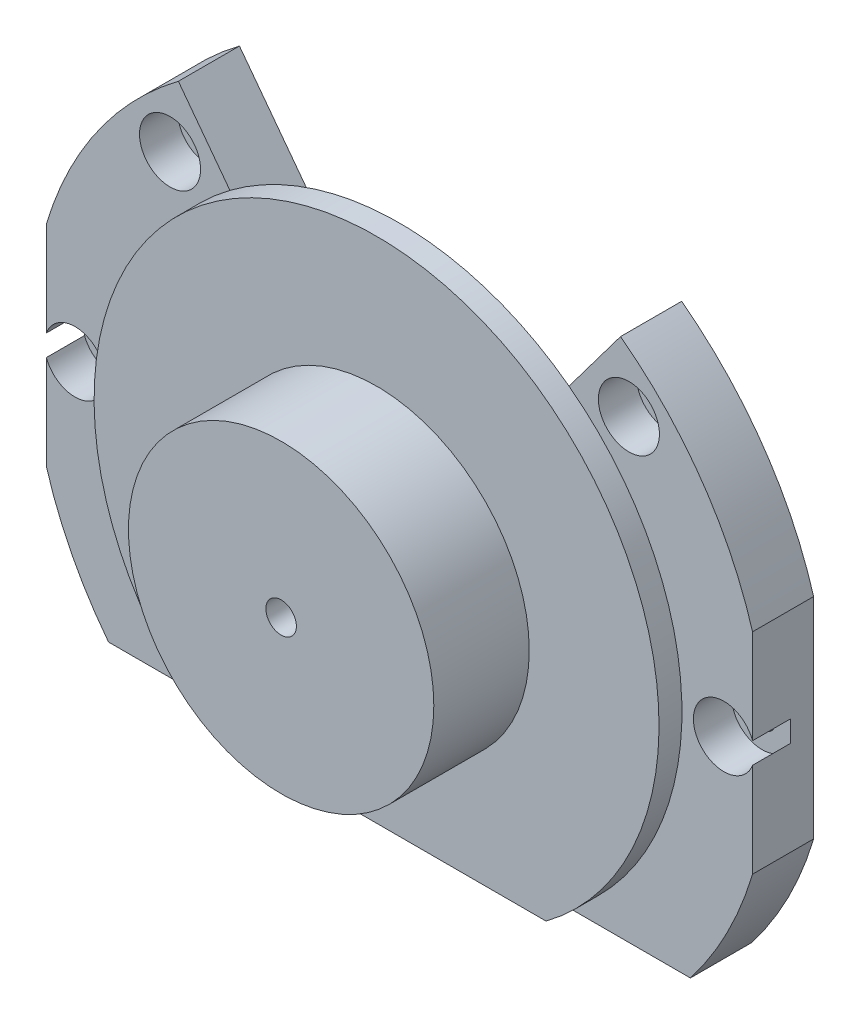
SolidWorks part; units mm, degrees
ref_plane "Front Plane" through (0, 0, 0) normal (0, 0, 1) x (1, 0, 0)
ref_plane "Top Plane" through (0, 0, 0) normal (0, 1, 0) x (1, 0, 0)
ref_plane "Right Plane" through (0, 0, 0) normal (1, 0, 0) x (0, 0, -1)
sketch "Sketch1" plane through (0, 0, 0) normal (0, 0, 1) x (1, 0, 0)
  circle A0 centre (0, 0) radius 48.25
extrude "Boss-Extrude1" add sketch "Sketch1" against normal blind 8 contours A0
sketch "Sketch2" plane through (0, 0, 0) normal (0, 0, 1) x (1, 0, 0)
  line L1 (-63.412, 28.4111) -> (-46.25, 28.4111)
  line L2 (-63.412, 28.4111) -> (-63.412, -28.4111)
  line L3 (-63.412, -28.4111) -> (-46.25, -28.4111)
  line L4 (-46.25, 28.4111) -> (-46.25, -28.4111)
  line L5 (46.25, 28.4111) -> (62.4025, 28.4111)
  line L6 (46.25, 28.4111) -> (46.25, -36.7758)
  line L7 (46.25, -36.7758) -> (62.4025, -36.7758)
  line L8 (62.4025, 28.4111) -> (62.4025, -36.7758)
  dimension "D1" = 92.5
  dimension "D2" = 46.25
extrude "Cut-Extrude1" cut sketch "Sketch2" against normal blind 8 contours L5 L8 L7 L6 | L1 L4 L3 L2
sketch "Sketch3" plane through (0, 0, 0) normal (0, 0, 1) x (1, 0, 0)
  circle A0 centre (0, 0) radius 30
extrude "Cut-Extrude2" cut sketch "Sketch3" against normal blind 8 contours A0
sketch "Sketch4" plane through (0, 0, 0) normal (0, 0, 1) x (1, 0, 0)
  circle A0 centre (-42.5, 0) radius 1.75
  dimension "D1" = 42.5
extrude "Cut-Extrude3" cut sketch "Sketch4" against normal blind 10
pattern_circular "CirPattern1" count 8 every 45 about axis through (0, 0, 0) along (0, 0, 1) of "Cut-Extrude3"
sketch "Sketch8" plane through (0, 0, 0) normal (0, 0, 1) x (1, 0, 0)
  line L0 (-28.9595, 38.5928) -> (0, 0)
  line L1 (0, 0) -> (28.9595, 38.5928)
  arc A0 (46.25, 13.7477) -> (-46.25, 13.7477) centre (0, 0) ccw construction
  arc A1 (-28.9595, 38.5928) -> (28.9595, 38.5928) centre (0, 0) cw
  circle A2 centre (-30.052, 30.052) radius 1.75 construction
  circle A3 centre (30.052, 30.052) radius 1.75 construction
  dimension "D1" = 6
  dimension "D3" = 0
  dimension "D2" = 6
extrude "Cut-Extrude4" cut sketch "Sketch8" against normal blind 10 contours L0 L1 A1
pattern_circular "CirPattern2" count 2 every 180 about axis through (0, 0, 0) along (0, 0, 1) of "Cut-Extrude4"
sketch "Sketch9" plane through (0, 0, 0) normal (0, 0, 1) x (1, 0, 0)
  circle A0 centre (-42.5, 0) radius 4
  circle A1 centre (-30.052, 30.052) radius 4
sketch "Sketch10" plane through (0, 0, 0) normal (0, 0, 1) x (1, 0, 0)
  circle A0 centre (42.5, 0) radius 4
  circle A1 centre (30.052, 30.052) radius 4
extrude "Cut-Extrude6" cut sketch "Sketch10" against normal blind 5
sketch "Sketch11" plane through (0, 0, 0) normal (0, 0, 1) x (1, 0, 0)
  circle A0 centre (0, 0) radius 37
extrude "Boss-Extrude2" add sketch "Sketch11" along normal blind 3 contours A0
sketch "Sketch12" plane through (0, 0, 3) normal (0, 0, 1) x (1, 0, 0)
  circle A0 centre (0, 0) radius 20
extrude "Boss-Extrude3" add sketch "Sketch12" along normal blind 12.5 contours A0
sketch "Sketch13" plane through (0, 0, 15.5) normal (0, 0, 1) x (1, 0, 0)
  circle A0 centre (0, 0) radius 2
extrude "Cut-Extrude8" cut sketch "Sketch13" against normal blind 38
sketch "Sketch14" plane through (0, 0, 0) normal (0, 0, -1) x (-1, 0, 0)
  line L1 (-2.0207, -3.5) -> (2.0207, -3.5)
  line L2 (2.0207, -3.5) -> (4.0415, 0)
  line L3 (4.0415, 0) -> (2.0207, 3.5)
  line L4 (2.0207, 3.5) -> (-2.0207, 3.5)
  line L5 (-2.0207, 3.5) -> (-4.0415, 0)
  line L6 (-4.0415, 0) -> (-2.0207, -3.5)
  circle A0 centre (0, 0) radius 3.5 construction
extrude "Cut-Extrude9" cut sketch "Sketch14" against normal blind 4 contours L4 L5 L6 L1 L2 L3
sketch "Sketch15" plane through (0, 0, -8) normal (0, 0, -1) x (-1, 0, 0)
  line L1 (-43.2095, -29.5945) -> (48.3941, -29.5945)
  line L2 (-43.2095, -29.5945) -> (-43.2095, -51.7102)
  line L3 (-43.2095, -51.7102) -> (48.3941, -51.7102)
  line L4 (48.3941, -29.5945) -> (48.3941, -51.7102)
extrude "Cut-Extrude10" cut sketch "Sketch15" against normal blind 34 contours L1 L4 L3 L2
extrude "Cut-Extrude11" cut sketch "Sketch9" against normal blind 5
sketch "Sketch16" plane through (0, 0, 0) normal (0, 0, 1) x (1, 0, 0)
  line L1 (-28.3629, -29.5945) -> (-33.3286, -29.5945)
  line L2 (-28.3629, -29.5945) -> (-28.3629, -27.3873)
  line L3 (-28.3629, -27.3873) -> (-33.3286, -27.3873)
  line L4 (-33.3286, -29.5945) -> (-33.3286, -27.3873)
  line L5 (31.7412, -29.5945) -> (27.667, -29.5945)
  line L6 (31.7412, -29.5945) -> (31.7412, -27.3873)
  line L7 (31.7412, -27.3873) -> (27.667, -27.3873)
  line L8 (27.667, -29.5945) -> (27.667, -27.3873)
extrude "Boss-Extrude4" add sketch "Sketch16" against normal blind 8
